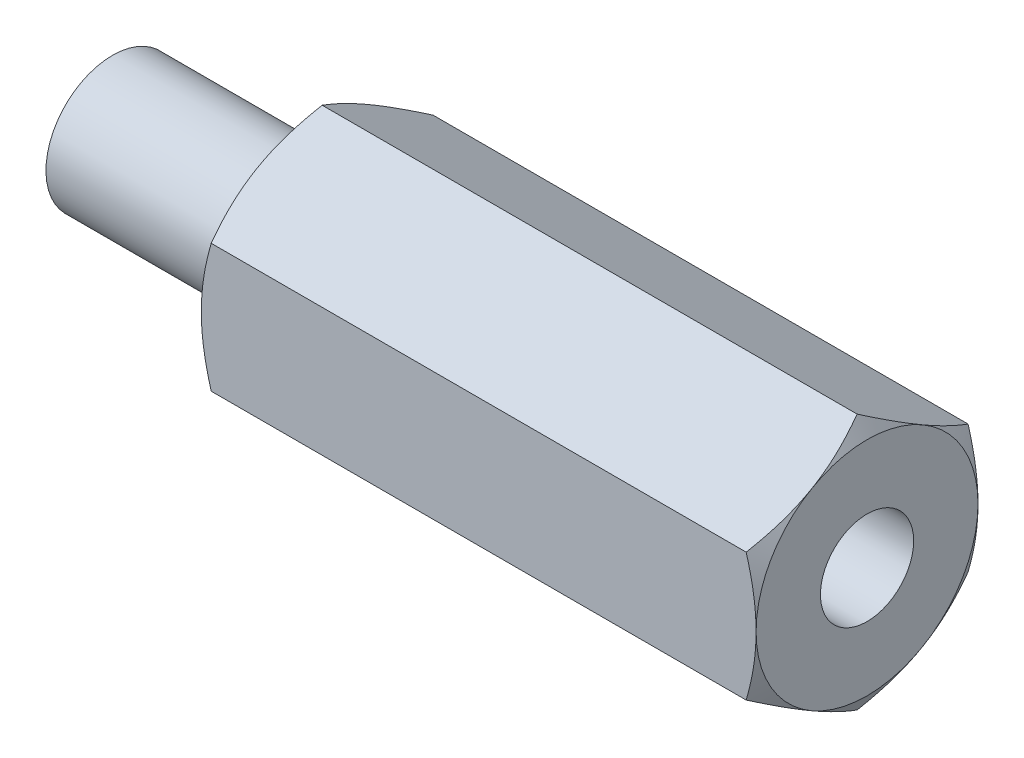
SolidWorks part; units mm, degrees
material "一般構造用鋼"
ref_plane "Front Plane" through (0, 0, 0) normal (0, 0, 1) x (1, 0, 0)
ref_plane "Top Plane" through (0, 0, 0) normal (0, 1, 0) x (1, 0, 0)
ref_plane "Right Plane" through (0, 0, 0) normal (1, 0, 0) x (0, 0, -1)
sketch "Sketch1" plane through (0, 0, 0) normal (1, 0, 0) x (0, 0, -1)
  line L1 (0, 5.7735) -> (-5, 2.8868)
  line L2 (-5, 2.8868) -> (-5, -2.8868)
  line L3 (-5, -2.8868) -> (0, -5.7735)
  line L4 (0, -5.7735) -> (5, -2.8868)
  line L5 (5, -2.8868) -> (5, 2.8868)
  line L6 (5, 2.8868) -> (0, 5.7735)
  circle A0 centre (0, 0) radius 5 construction
  dimension "B" = 10
  dimension "C" = 11.547
extrude "Boss-Extrude1" add sketch "Sketch1" along normal blind 25
sketch "Sketch2" plane through (0, 0, 0) normal (0, 0, 1) x (1, 0, 0)
  line L0 (0, 0) -> (25, 0) construction
  line L1 (25, 2.8868) -> (25, -2.8868) construction
  line L2 (0.4466, 5.7735) -> (0, 5.7735)
  line L3 (0, 5.7735) -> (0, 5)
  line L4 (0, 5) -> (0.4466, 5.7735)
  line L5 (0, 2.8868) -> (0, 5.7735) construction
  line L6 (25, 5.7735) -> (0, 5.7735) construction
  line L8 (25, 5) -> (25, 5.7735)
  line L9 (25, 5.7735) -> (24.5534, 5.7735)
  line L10 (24.5534, 5.7735) -> (25, 5)
  line L11 (25, 5.7735) -> (25, 2.8868) construction
  dimension "D1" = 30
revolve "Cut-Revolve1" cut sketch "Sketch2" angle 360 about L0
sketch "Sketch3" plane through (0, 0, 0) normal (0, 0, 1) x (1, 0, 0)
  line L0 (0, 0) -> (-9, 0) construction
  line L1 (0, 0) -> (0, 3)
  line L2 (0, 5.7735) -> (0, 5) construction
  line L3 (-2, 3) -> (-2, 0) construction
  line L4 (0, 3) -> (-9, 3)
  line L5 (-9, 3) -> (-9, 0)
  line L6 (-9, 0) -> (0, 0)
  dimension "A" = 2
  dimension "M" = 6
  dimension "F" = 9
revolve "Revolve1" add sketch "Sketch3" angle 360 about L0
cosmetic thread "Cosmetic Thread1" parameters "D1"=7, "TD_s"=4.917
hole_wizard "Tapped Hole1" positions "Sketch5" profile "Sketch4" tap size "M5x0.8" standard "JIS"
sketch "Sketch5" plane through (25, 0, 0) normal (1, 0, 0) x (0, 0, -1)
  point P0 (0, 0)
sketch "Sketch4" plane through (25, 0, 0) normal (0, 1, 0) x (0, 0, -1)
  line L0 (0, 0) -> (0, 15.2618)
  line L1 (0, 15.2618) -> (2.1, 14)
  line L2 (2.1, 14) -> (2.1, 0)
  line L5 (2.1, 0) -> (0, 0)
  line L10 (0, 15.2618) -> (-2.1, 14) construction
  line L11 (0, 0) -> (0, 15.2618) construction
  dimension "Tap Drill Dia." = 4.2
  dimension "Tap Drill Depth" = 14
  dimension "Drill Angle" = 118
cosmetic thread "Hole Thread1" parameters "Nx2"=10, "N"=5
fillet "Fillet1" radius 0.5 1 edges at (0, 3, 0)
sketch "Sketch6" [suppressed] plane through (0, 0, 0) normal (0, 0, 1) x (1, 0, 0)
  line L0 (0, 0) -> (-5, 0) construction
  line L1 (-5, 1.5) -> (-5, -1.5) construction
  line L2 (0, 3.4641) -> (0, 1.7321) construction
  line L3 (-1.5, 3.4641) -> (0, 3.4641)
  line L4 (-1.5, 3.4641) -> (-1.5, 1.15)
  line L6 (0, 3.4641) -> (0, 1.15)
  line L7 (-1.5, 1.5) -> (-1.5, 0) construction
  line L8 (14.7321, 3.4641) -> (0.2679, 3.4641) construction
  line L9 (0, 1.15) -> (-1.5, 1.15)
  dimension "MC" = 2.3
revolve "Cut-Revolve2" [suppressed] cut sketch "Sketch6" angle 360 about L0
hole_wizard "Tapped Hole2" [suppressed] positions "Sketch10" profile "Sketch9" tap size "M3x0.5" standard "JIS"
sketch "Sketch10" [suppressed] plane through (15, 0, 0) normal (1, 0, 0) x (0, 0, -1)
  point P0 (0, 0)
sketch "Sketch9" [suppressed] plane through (15, 0, 0) normal (0, 1, 0) x (0, 0, -1)
  line L0 (0, 0) -> (0, 12.2511)
  line L1 (0, 12.2511) -> (1.25, 11.5)
  line L2 (1.25, 11.5) -> (1.25, 0)
  line L5 (1.25, 0) -> (0, 0)
  line L10 (0, 12.2511) -> (-1.25, 11.5) construction
  line L11 (0, 0) -> (0, 12.2511) construction
  dimension "Tap Drill Dia." = 2.5
  dimension "Tap Drill Depth" = 11.5
  dimension "Drill Angle" = 118
cosmetic thread "Hole Thread2" [suppressed] parameters "Nx3"=9, "ND"=3
equation "\"D1@Cosmetic Thread1\" = \"F@Sketch3\" - \"A@Sketch3\""
